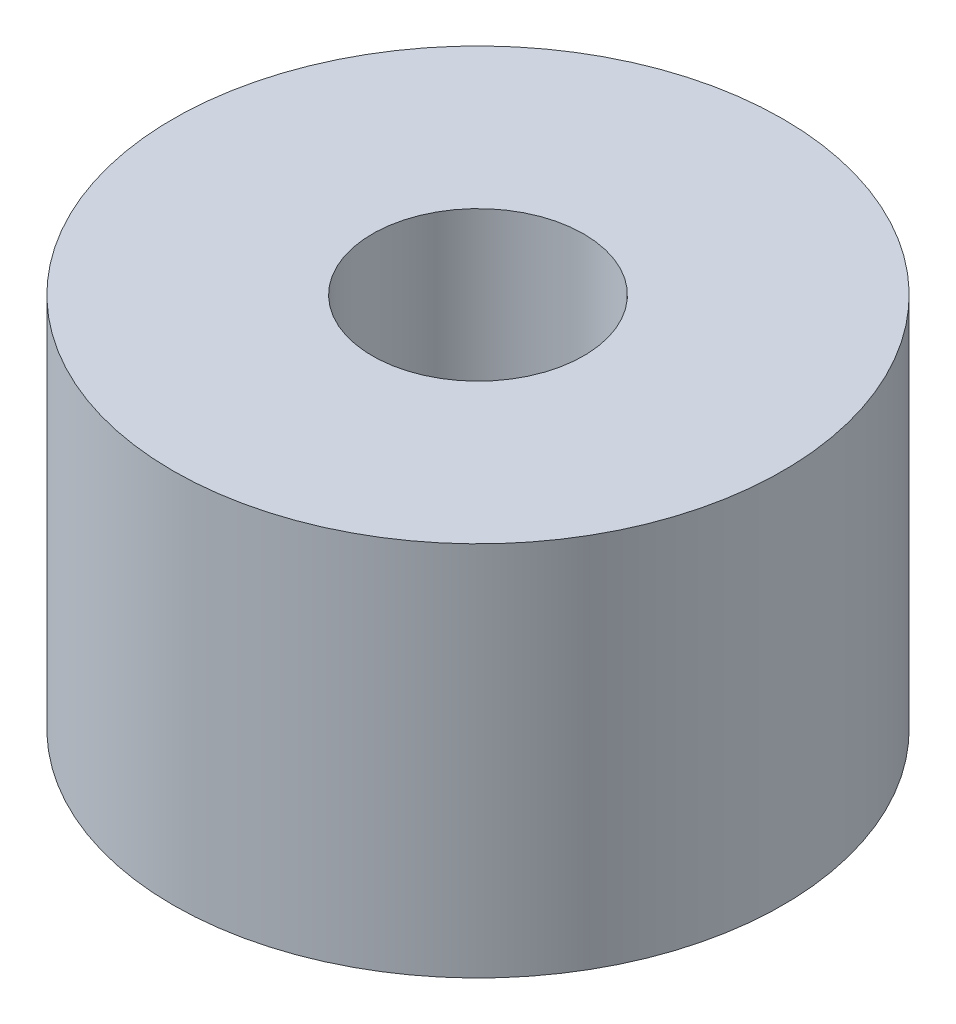
SolidWorks part; units mm, degrees
ref_plane "Front Plane" through (0, 0, 0) normal (0, 0, 1) x (1, 0, 0)
ref_plane "Top Plane" through (0, 0, 0) normal (0, 1, 0) x (1, 0, 0)
ref_plane "Right Plane" through (0, 0, 0) normal (1, 0, 0) x (0, 0, -1)
sketch "Sketch1" plane through (0, 0, 0) normal (0, 1, 0) x (1, 0, 0)
  circle A0 centre (0, 0) radius 9.525
  circle A1 centre (0, 0) radius 3.302
  dimension "D1" = 6.604
  dimension "D2" = 19.05
extrude "Boss-Extrude1" add sketch "Sketch1" along normal blind 7.62
sketch "Sketch2" plane through (0, 7.62, 0) normal (0, 1, 0) x (1, 0, 0)
  circle A0 centre (0, 0) radius 3.302 construction
  circle A1 centre (0, 0) radius 9.525
  circle A2 centre (0, 0) radius 9.525
  circle A3 centre (0, 0) radius 3.302
  dimension "D1" = 0
extrude "Boss-Extrude2" add sketch "Sketch2" along normal blind 4.1275
